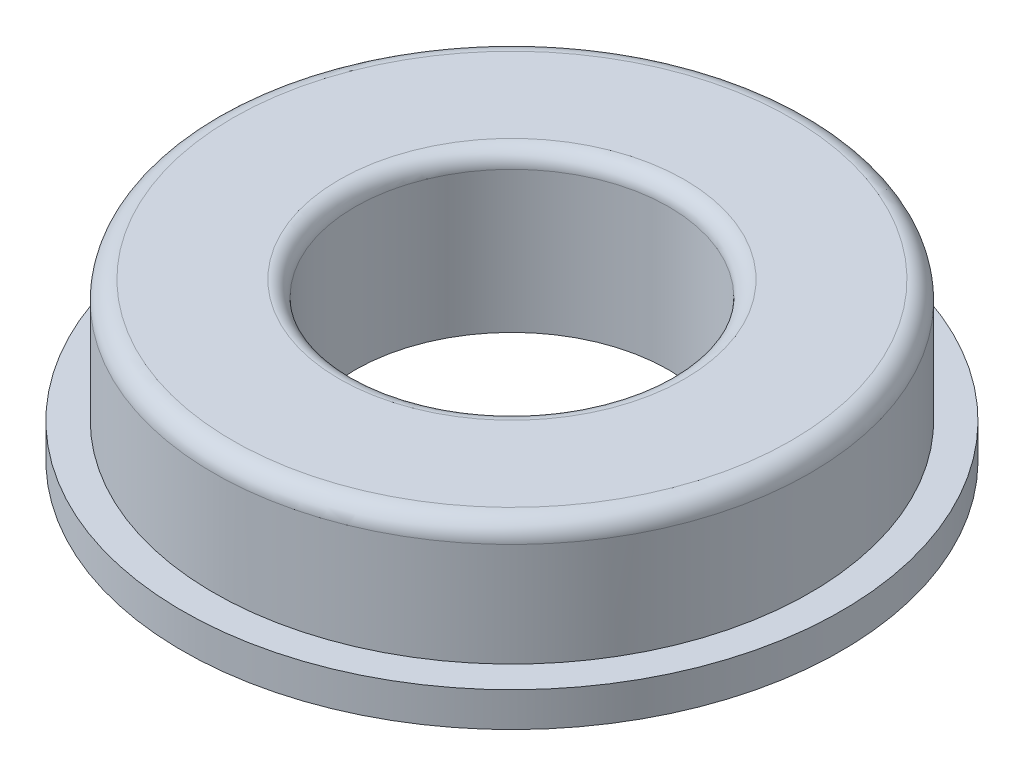
SolidWorks part; units mm, degrees
material "合金钢"
ref_plane "前视基准面" through (0, 0, 0) normal (0, 0, 1) x (1, 0, 0)
ref_plane "上视基准面" through (0, 0, 0) normal (0, 1, 0) x (1, 0, 0)
ref_plane "右视基准面" through (0, 0, 0) normal (1, 0, 0) x (0, 0, -1)
sketch "草图2" plane through (0, 0, 0) normal (0, 0, 1) x (1, 0, 0)
  line L0 (0, 0) -> (4.5, 0)
  line L1 (4.5, 0) -> (4.5, -3.9)
  line L2 (4.5, -3.9) -> (5.5, -3.9)
  line L3 (5.5, -3.9) -> (5.5, -5)
  line L4 (5.5, -5) -> (0, -5)
  line L5 (0, -5) -> (0, 0)
  line L6 (-5, 0) -> (-5, -3.5949) construction
  dimension "D1" = 5
  dimension "D2" = 4.5
  dimension "D3" = 5.5
  dimension "D4" = 3.9
  dimension "D5" = 1.1
revolve "旋转1" add sketch "草图2" angle 360 about L6
fillet "圆角1" radius 0.6 1 edges at (-14.5, 0, 0)
fillet "圆角2" radius 0.5 1 edges at (-10, 0, 0)
